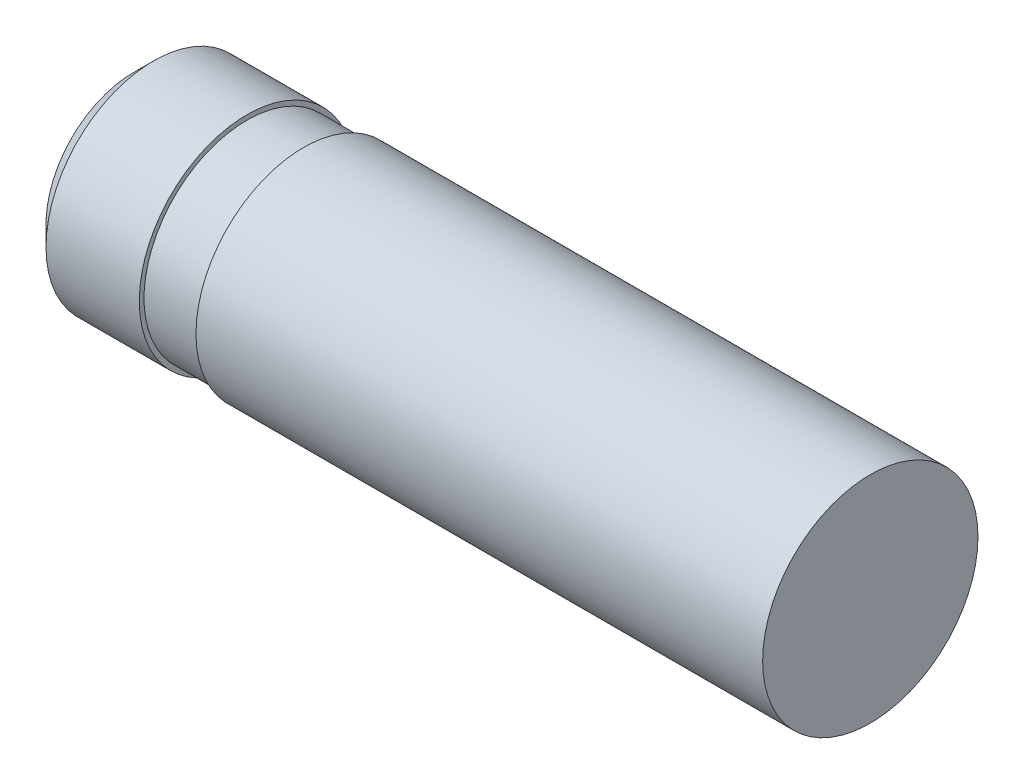
SolidWorks part; units mm, degrees
ref_plane "Front Plane" through (0, 0, 0) normal (0, 0, 1) x (1, 0, 0)
ref_plane "Top Plane" through (0, 0, 0) normal (0, 1, 0) x (1, 0, 0)
ref_plane "Right Plane" through (0, 0, 0) normal (1, 0, 0) x (0, 0, -1)
sketch "Sketch1" plane through (0, 0, 0) normal (0, 0, 1) x (1, 0, 0)
  line L0 (0, 0) -> (0, 1.5464)
  line L1 (0, 1.5464) -> (0.3536, 1.9)
  line L2 (0.3536, 1.9) -> (2, 1.9)
  line L3 (2, 1.9) -> (2, 1.8166)
  line L4 (2, 1.8166) -> (3, 1.8166)
  line L5 (3, 1.8166) -> (3, 1.9)
  line L6 (3, 1.9) -> (13, 1.9)
  line L7 (13, 1.9) -> (13, 0)
  line L8 (13, 0) -> (0, 0)
  point P3 (2, 1.8583)
  dimension "D1" = 13
  dimension "D2" = 1
  dimension "D3" = 2
  dimension "D4" = 10
  dimension "D5" = 1.9
  dimension "D6" = 0.5
  dimension "D7" = 45
revolve "Revolve1" add sketch "Sketch1" angle 360 about L8
